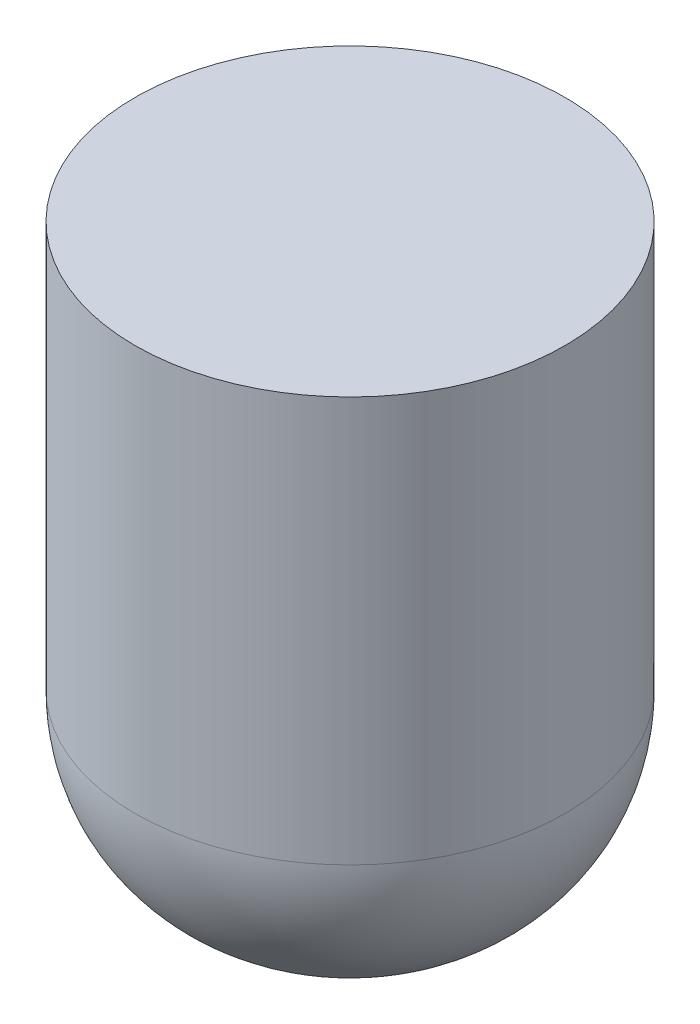
SolidWorks part; units mm, degrees
ref_plane "Front Plane" through (0, 0, 0) normal (0, 0, 1) x (1, 0, 0)
ref_plane "Top Plane" through (0, 0, 0) normal (0, 1, 0) x (1, 0, 0)
ref_plane "Right Plane" through (0, 0, 0) normal (1, 0, 0) x (0, 0, -1)
sketch "Sketch2" plane through (0, 0, 0) normal (1, 0, 0) x (0, 0, -1)
  line L0 (0, 0) -> (0, -358.8195) construction
  line L1 (0, 0) -> (-130.175, 0)
  line L2 (-130.175, 0) -> (-130.175, -245.3888)
  line L3 (0, 0) -> (0, -358.8195)
  arc A0 (-130.175, -245.3888) -> (0, -358.8195) centre (-15.6674, -245.3888) ccw
  point P6 (0, 0)
  dimension "D1" = 130.175
revolve "Revolve2" add sketch "Sketch2" angle 360 about L0
